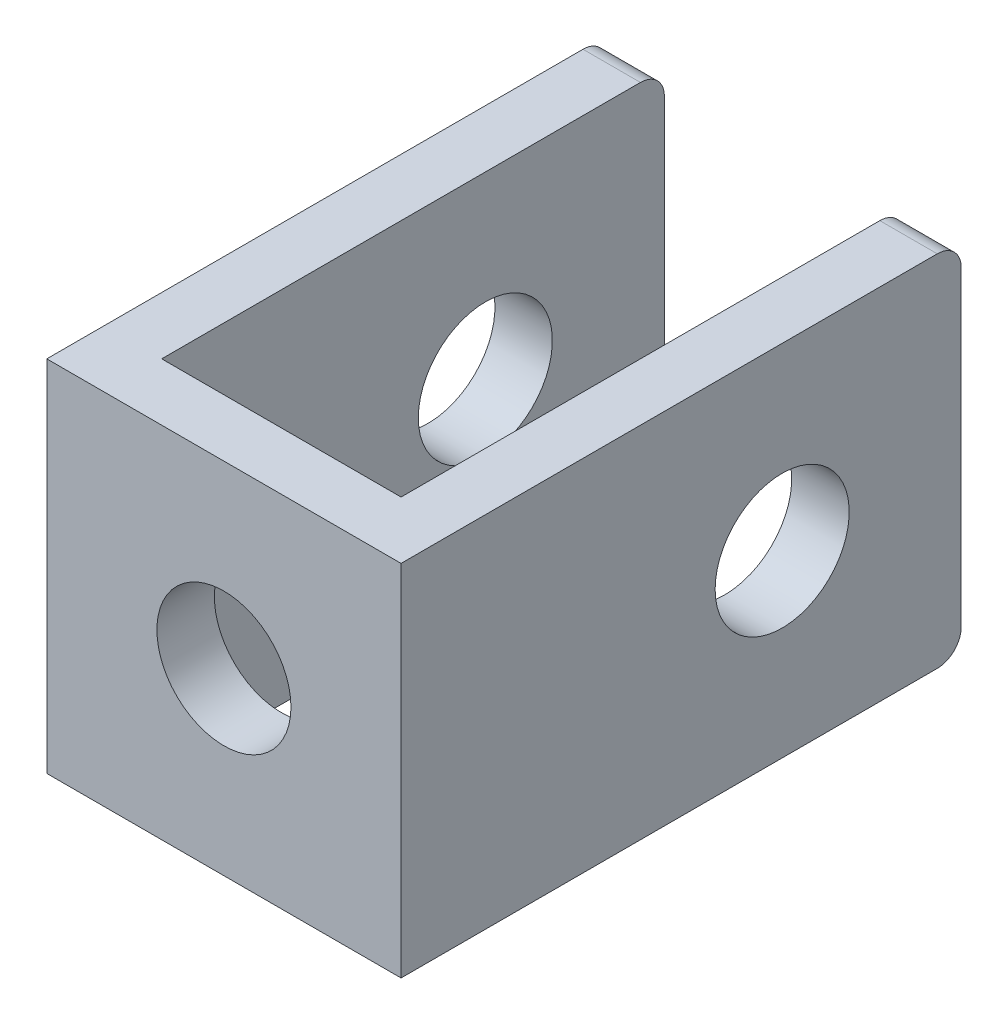
SolidWorks part; units mm, degrees
ref_plane "Front Plane" through (0, 0, 0) normal (0, 0, 1) x (1, 0, 0)
ref_plane "Top Plane" through (0, 0, 0) normal (0, 1, 0) x (1, 0, 0)
ref_plane "Right Plane" through (0, 0, 0) normal (1, 0, 0) x (0, 0, -1)
ref_plane "Plane1" through (4.699, 0, 0) normal (1, 0, 0) x (0, 0, -1)
sketch "Sketch1" plane through (4.699, 0, 0) normal (1, 0, 0) x (0, 0, -1)
  line L0 (-7.4295, 0) -> (7.4295, 0)
  line L1 (7.4295, 0) -> (7.4295, 9.525)
  line L2 (7.4295, 9.525) -> (-7.4295, 9.525)
  line L3 (-7.4295, 9.525) -> (-7.4295, 0)
extrude "Boss-Extrude1" add sketch "Sketch1" against normal blind 9.398
sketch "Sketch2" plane through (0, 0, 0) normal (0, -1, 0) x (1, 0, 0)
  line L0 (-3.175, -7.4295) -> (3.175, -7.4295)
  line L1 (3.175, -7.4295) -> (3.175, 5.9055)
  line L2 (3.175, 5.9055) -> (-3.175, 5.9055)
  line L3 (-3.175, 5.9055) -> (-3.175, -7.4295)
extrude "Cut-Extrude1" cut sketch "Sketch2" against normal through all
hole_wizard "#5 Clearance Hole1" positions "Sketch4" profile "Sketch3" hole size "#5" standard "ANSI Inch"
sketch "Sketch4" plane through (-4.699, 0, 0) normal (-1, 0, 0) x (0, 0, 1)
  point P0 (-2.6797, 4.7625)
sketch "Sketch3" plane through (-4.699, 4.7625, -2.6797) normal (0, 1, 0) x (0, 0, 1)
  line L0 (0, 0) -> (0, 1.524)
  line L1 (0, 1.524) -> (1.778, 1.524)
  line L2 (1.778, 1.524) -> (1.778, 0)
  line L5 (1.778, 0) -> (0, 0)
  line L11 (0, -6.35) -> (0, 107.95) construction
  dimension "Thru Hole Dia." = 3.556
  dimension "Thru Hole Depth" = 1.524
hole_wizard "#5 Clearance Hole2" positions "Sketch6" profile "Sketch5" hole size "#5" standard "ANSI Inch"
sketch "Sketch6" plane through (0, 0, 7.4295) normal (0, 0, 1) x (1, 0, 0)
  point P0 (0, 4.7625)
sketch "Sketch5" plane through (0, 4.7625, 7.4295) normal (1, 0, 0) x (0, -1, 0)
  line L0 (0, 0) -> (0, 14.859)
  line L1 (0, 14.859) -> (1.778, 14.859)
  line L2 (1.778, 14.859) -> (1.778, 0)
  line L5 (1.778, 0) -> (0, 0)
  line L11 (0, -6.35) -> (0, 107.95) construction
  dimension "Thru Hole Dia." = 3.556
  dimension "Thru Hole Depth" = 14.859
hole_wizard "#5 Clearance Hole3" positions "Sketch8" profile "Sketch7" hole size "#5" standard "ANSI Inch"
sketch "Sketch8" plane through (3.175, 0, 0) normal (-1, 0, 0) x (0, 0, 1)
  point P0 (-2.6797, 4.7625)
sketch "Sketch7" plane through (3.175, 4.7625, -2.6797) normal (0, 1, 0) x (0, 0, 1)
  line L0 (0, 0) -> (0, 1.524)
  line L1 (0, 1.524) -> (1.778, 1.524)
  line L2 (1.778, 1.524) -> (1.778, 0)
  line L5 (1.778, 0) -> (0, 0)
  line L11 (0, -6.35) -> (0, 107.95) construction
  dimension "Thru Hole Dia." = 3.556
  dimension "Thru Hole Depth" = 1.524
fillet "Fillet1" radius 0.635 4 edges at (-3.937, 0, -7.4295) (-3.937, 9.525, -7.4295) (3.937, 9.525, -7.4295) (3.937, 0, -7.4295)
